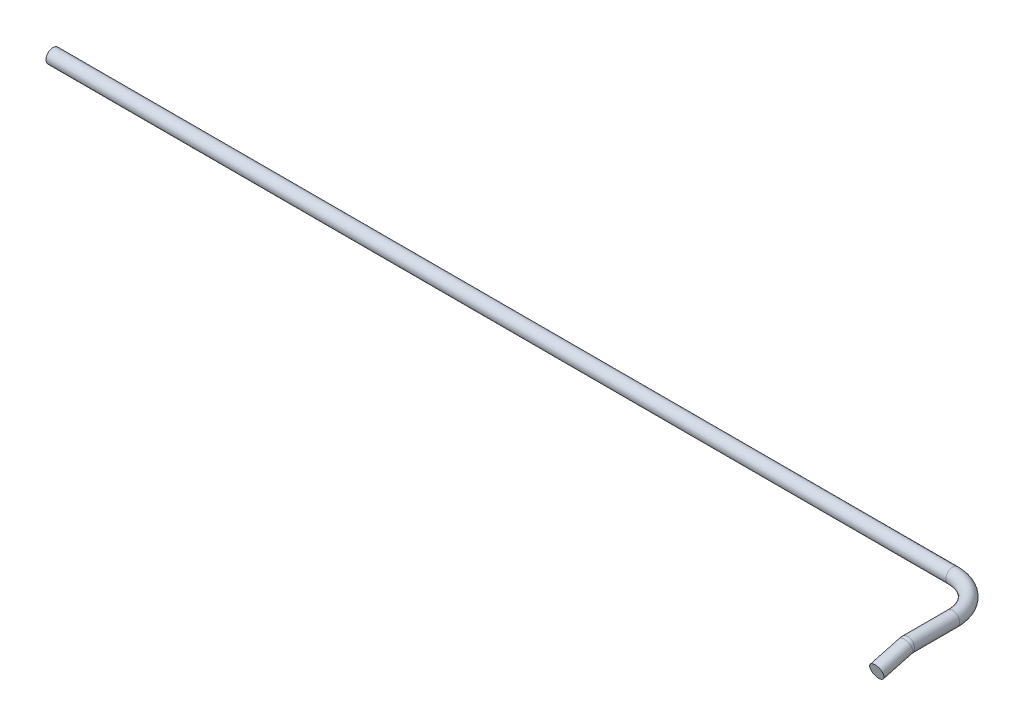
SolidWorks part; units mm, degrees
material "2024 Alloy"
ref_plane "Front Plane" through (0, 0, 0) normal (0, 0, 1) x (1, 0, 0)
ref_plane "Top Plane" through (0, 0, 0) normal (0, 1, 0) x (1, 0, 0)
ref_plane "Right Plane" through (0, 0, 0) normal (1, 0, 0) x (0, 0, -1)
sketch "Sketch1" plane through (0, 0, 0) normal (0, 0, 1) x (1, 0, 0)
  circle A0 centre (0, 0) radius 1.1811
  dimension "D1" = 2.3622
extrude "RodEnd" add sketch "Sketch1" against normal blind 7.62
sketch "Sketch2" plane through (0, 0, 0) normal (0, 0, 1) x (1, 0, 0)
  line L1 (-1.1811, -0.762) -> (1.1811, -0.762)
  line L2 (-1.1811, -0.762) -> (-1.1811, 0.762)
  line L3 (-1.1811, 0.762) -> (1.1811, 0.762)
  line L4 (1.1811, -0.762) -> (1.1811, 0.762)
  line L5 (-1.1811, -0.762) -> (1.1811, 0.762) construction
  line L6 (-1.1811, 0.762) -> (1.1811, -0.762) construction
  line L7 (-3.175, -1.1811) -> (3.175, -1.1811)
  line L8 (-3.175, -1.1811) -> (-3.175, 1.1811)
  line L9 (-3.175, 1.1811) -> (3.175, 1.1811)
  line L10 (3.175, -1.1811) -> (3.175, 1.1811)
  line L11 (-3.175, -1.1811) -> (3.175, 1.1811) construction
  line L12 (-3.175, 1.1811) -> (3.175, -1.1811) construction
  circle A0 centre (0, 0) radius 1.1811 construction
  point P0 (0, 0)
  point P8 (0, 0)
  dimension "D1" = 1.524
  dimension "D2" = 6.35
extrude "Flats" [suppressed] cut sketch "Sketch2" against normal blind 5.715
sketch "Sketch3" [suppressed] plane through (0, 0.762, 0) normal (0, 1, 0) x (1, 0, 0)
  line L0 (0.968, 0) -> (-0.968, 0) construction
  circle A0 centre (0, 1.27) radius 0.5715
  dimension "D2" = 1.143
  dimension "D1" = 1.27
extrude "Hole" [suppressed] cut sketch "Sketch3" against normal through all
sketch "Sketch4" plane through (0, 0, -7.62) normal (0, 0, -1) x (-1, 0, 0)
  line L0 (6.35, 0) -> (6.35, 2.0828) construction
  circle A0 centre (0, 0) radius 1.1811
  circle A1 centre (0, 0) radius 1.1811 construction
  dimension "D1" = 6.35
revolve "Revolve1" add sketch "Sketch4" angle 90 about L0
sketch "Sketch5" plane through (-6.35, 0, 0) normal (-1, 0, 0) x (0, 0, 1)
  circle A0 centre (-13.97, 0) radius 1.1811
  circle A1 centre (-13.97, 0) radius 1.1811 construction
extrude "Boss-Extrude1" add sketch "Sketch5" along normal blind 152.4
sketch "Sketch6" plane through (0, 0, 0) normal (0, 0, 1) x (1, 0, 0)
  line L0 (0, -1.27) -> (2.4305, -1.27) construction
  circle A0 centre (0, 0) radius 1.1811
  circle A1 centre (0, 0) radius 1.1811 construction
  dimension "D1" = 1.27
revolve "Revolve2" add sketch "Sketch6" angle 15 about L0
sketch "Sketch7" plane through (0, -0.0851, 0.3175) normal (0, -0.2588, 0.9659) x (-1, 0, 0)
  circle A0 centre (0, -0.0433) radius 1.1811
  circle A1 centre (0, -0.0433) radius 1.1811 construction
extrude "Boss-Extrude2" add sketch "Sketch7" along normal blind 5.08
